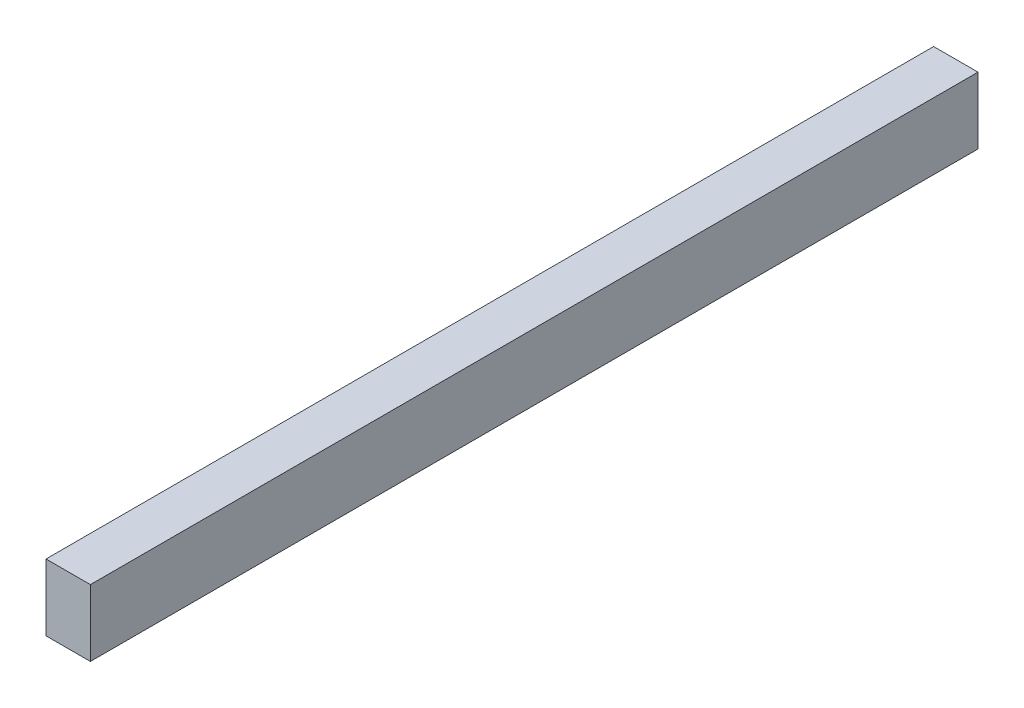
SolidWorks part; units mm, degrees
ref_plane "Płaszczyzna przednia" through (0, 0, 0) normal (0, 0, 1) x (1, 0, 0)
ref_plane "Płaszczyzna górna" through (0, 0, 0) normal (0, 1, 0) x (1, 0, 0)
ref_plane "Płaszczyzna prawa" through (0, 0, 0) normal (1, 0, 0) x (0, 0, -1)
sketch "Szkic1" plane through (0, 0, 0) normal (0, 0, 1) x (1, 0, 0)
  line L1 (0, 0) -> (10, 0)
  line L2 (0, 0) -> (0, 15)
  line L3 (0, 15) -> (10, 15)
  line L4 (10, 0) -> (10, 15)
  dimension "D1" = 15
  dimension "D2" = 10
extrude "Dodanie-wyciągnięcie1" add sketch "Szkic1" along normal blind 200
sketch "Szkic2" plane through (0, 0, 0) normal (0, 1, 0) x (1, 0, 0)
  line L0 (0, -150) -> (10, -150)
  line L1 (0, -200) -> (0, 0) construction
  line L2 (10, -200) -> (10, 0) construction
  line L3 (10, -200) -> (0, -200) construction
  dimension "D1" = 50
split line "Linia podziałowa1"
